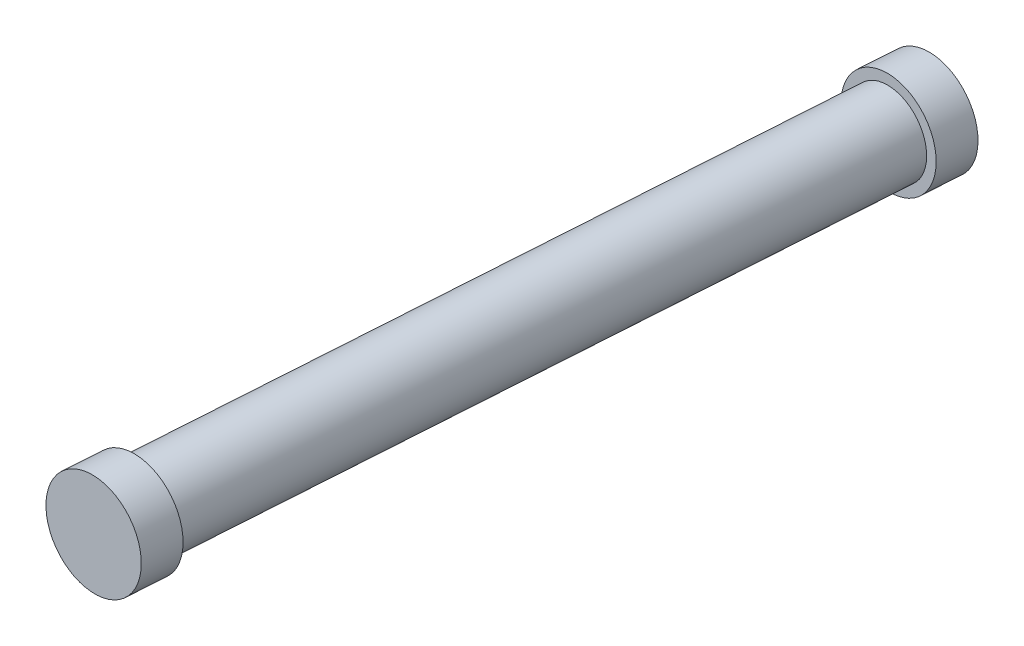
SolidWorks part; units mm, degrees
ref_plane "Front Plane" through (0, 0, 0) normal (0, 0, 1) x (1, 0, 0)
ref_plane "Top Plane" through (0, 0, 0) normal (0, 1, 0) x (1, 0, 0)
ref_plane "Right Plane" through (0, 0, 0) normal (1, 0, 0) x (0, 0, -1)
sketch "Sketch1" plane through (-3.7743, 1.5051, 80.822) normal (-0.0466, 0.0186, 0.9987) x (0.9989, 0.0009, 0.0466)
  circle A0 centre (1103.9983, -68.0193) radius 1
extrude "Boss-Extrude1" add sketch "Sketch1" against normal blind 18
ref_plane "Plane1" through (-3.3546, 1.3377, 71.8334) normal (-0.0466, 0.0186, 0.9987) x (0.9989, 0.0009, 0.0466)
sketch "Sketch2" plane through (-3.7743, 1.5051, 80.822) normal (-0.0466, 0.0186, 0.9987) x (0.9989, 0.0009, 0.0466)
  circle A0 centre (1103.9983, -68.0193) radius 1.25
  dimension "D1" = 2.5
extrude "Boss-Extrude2" add sketch "Sketch2" along normal blind 1
mirror "Mirror1" about plane through (-3.3546, 1.3377, 71.8334) normal (-0.0466, 0.0186, 0.9987) of "Boss-Extrude2"
